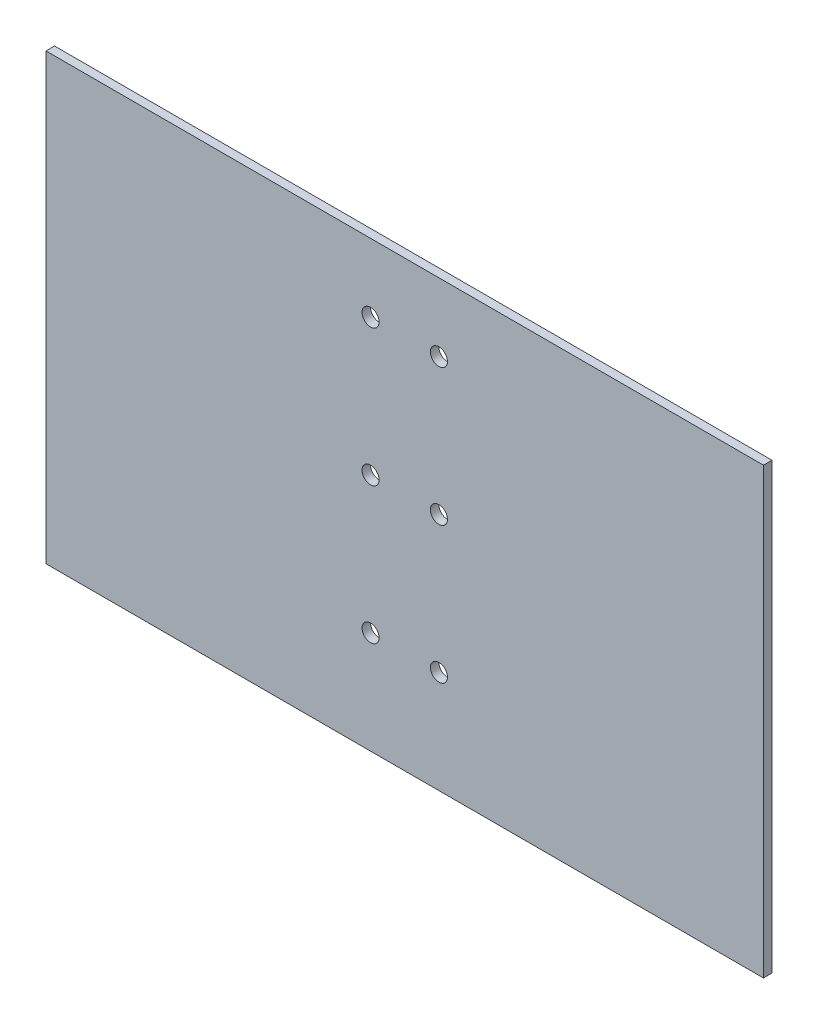
SolidWorks part; units mm, degrees
ref_plane "Front Plane" through (0, 0, 0) normal (0, 0, 1) x (1, 0, 0)
ref_plane "Top Plane" through (0, 0, 0) normal (0, 1, 0) x (1, 0, 0)
ref_plane "Right Plane" through (0, 0, 0) normal (1, 0, 0) x (0, 0, -1)
sketch "Sketch1" plane through (0, 0, 0) normal (0, 0, 1) x (1, 0, 0)
  line L1 (-127, -76.2) -> (127, -76.2)
  line L2 (-127, -76.2) -> (-127, 76.2)
  line L3 (-127, 76.2) -> (127, 76.2)
  line L4 (127, -76.2) -> (127, 76.2)
  line L5 (-127, -76.2) -> (127, 76.2) construction
  line L6 (-127, 76.2) -> (127, -76.2) construction
  circle A0 centre (0, 0) radius 53.34
  dimension "D1" = 127
  dimension "D3" = 106.68
  dimension "D2" = 76.2
extrude "Boss-Extrude1" add sketch "Sketch1" along normal blind 6.35
hole_wizard "3/8 Clearance Hole1" [suppressed] positions "Sketch5" profile "Sketch6" hole size "3/8" standard "ANSI Inch"
sketch "Sketch5" plane through (0, 0, 6.35) normal (0, 0, 1) x (1, 0, 0)
  circle A0 centre (0, 0) radius 67.31
  point P10 (-67.31, 0)
  point P18 (-54.4549, 39.5638)
  point P19 (-20.7999, 64.0156)
  point P20 (20.7999, 64.0156)
  point P21 (54.4549, 39.5638)
  point P22 (67.31, 0)
  point P23 (54.4549, -39.5638)
  point P24 (20.7999, -64.0156)
  point P25 (-20.7999, -64.0156)
  point P26 (-54.4549, -39.5638)
  dimension "D1" = 134.62
  dimension "D2" = 10
sketch "Sketch6" plane through (-54.4549, -39.5638, 6.35) normal (1, 0, 0) x (0, -1, 0)
  line L0 (0, 0) -> (0, 6.35)
  line L1 (0, 6.35) -> (5.0419, 6.35)
  line L2 (5.0419, 6.35) -> (5.0419, 0.635)
  line L3 (5.0419, 0.635) -> (5.6769, 0)
  line L5 (5.6769, 0) -> (0, 0)
  line L6 (-5.0419, 0.635) -> (-5.6769, 0) construction
  line L11 (0, -6.35) -> (0, 107.95) construction
  dimension "Thru Hole Dia." = 10.0838
  dimension "Thru Hole Depth" = 6.35
  dimension "Near C'Sink Dia." = 11.3538
  dimension "Near C'Sink Angle" = 90
hole_wizard "#4 Clearance Hole1" [suppressed] positions "Sketch8" profile "Sketch10" hole size "#4" standard "ANSI Inch"
sketch "Sketch8" plane through (0, 0, 0) normal (0, 0, -1) x (-1, 0, 0)
  line L0 (127, 0) -> (-127, 0) construction
  line L1 (127, 76.2) -> (127, -76.2) construction
  line L2 (-127, -76.2) -> (-127, 76.2) construction
  line L4 (0, 76.2) -> (0, -76.2) construction
  line L5 (-127, 76.2) -> (127, 76.2) construction
  line L6 (127, -76.2) -> (-127, -76.2) construction
  point P9 (67.31, 64.0156)
  point P30 (67.31, -64.0156)
  point P31 (-67.31, -64.0156)
  point P32 (-67.31, 64.0156)
  dimension "D1" = 67.31
  dimension "D2" = 12.1844
sketch "Sketch10" plane through (-67.31, 64.0156, 0) normal (1, 0, 0) x (0, 1, 0)
  line L0 (0, 0) -> (0, 6.35)
  line L1 (0, 6.35) -> (1.6319, 6.35)
  line L2 (1.6319, 6.35) -> (1.6319, 0)
  line L5 (1.6319, 0) -> (0, 0)
  line L11 (0, -6.35) -> (0, 107.95) construction
  dimension "Thru Hole Dia." = 3.2639
  dimension "Thru Hole Depth" = 6.35
sketch "Sketch11" plane through (0, 0, 0) normal (0, 0, -1) x (-1, 0, 0)
  line L0 (127, 76.2) -> (127, -76.2) construction
  line L1 (127, 76.2) -> (127, -76.2) construction
  line L2 (127, 0) -> (107.95, 0) construction
  line L4 (0, 76.2) -> (0, -76.2) construction
  line L5 (-127, 76.2) -> (127, 76.2) construction
  line L6 (127, -76.2) -> (-127, -76.2) construction
  circle A0 centre (107.95, 0) radius 4.1656
  circle A1 centre (-107.95, 0) radius 4.1656
  dimension "D1" = 8.3312
  dimension "D2" = 19.05
extrude "Cut-Extrude1" [suppressed] cut sketch "Sketch11" against normal through all
sketch "Sketch12" plane through (0, 0, 6.35) normal (0, 0, 1) x (1, 0, 0)
  line L0 (127, 76.2) -> (-127, 76.2) construction
  line L1 (101.6, -76.2) -> (-101.6, -76.2)
  line L2 (101.6, -76.2) -> (101.6, 76.2)
  line L3 (101.6, 76.2) -> (-101.6, 76.2)
  line L4 (-101.6, -76.2) -> (-101.6, 76.2)
  line L5 (101.6, -76.2) -> (-101.6, 76.2) construction
  line L6 (101.6, 76.2) -> (-101.6, -76.2) construction
  line L7 (-127, 76.2) -> (-127, -76.2) construction
  point P0 (0, 0)
  dimension "D1" = 25.4
extrude "Cut-Extrude2" [suppressed] cut sketch "Sketch12" against normal through all flip side to cut
sketch "Sketch13" plane through (0, 0, 6.35) normal (0, 0, 1) x (1, 0, 0)
  circle A0 centre (0, 0) radius 53.34 construction
  circle A1 centre (0, 0) radius 53.34
extrude "Boss-Extrude2" add sketch "Sketch13" against normal blind 6.35
sketch "Sketch16" [suppressed] plane through (0, 0, 6.35) normal (0, 0, 1) x (1, 0, 0)
  circle A1 centre (0, 0) radius 63.5
  dimension "D1" = 127
extrude "Cut-Extrude3" [suppressed] cut sketch "Sketch16" against normal blind 6.35
sketch "Sketch17" [suppressed] plane through (0, 0, 6.35) normal (0, 0, 1) x (1, 0, 0)
  line L0 (0, 139.7) -> (0, -139.7) construction
  line L1 (-139.7, 139.7) -> (-146.05, 139.7)
  line L2 (-139.7, 139.7) -> (-139.7, -76.2)
  line L3 (-139.7, -76.2) -> (-146.05, -76.2)
  line L4 (-146.05, 139.7) -> (-146.05, -76.2)
  line L5 (139.7, 139.7) -> (-139.7, 139.7) construction
  line L6 (-139.7, -139.7) -> (139.7, -139.7) construction
  line L7 (139.7, -76.2) -> (146.05, -76.2)
  line L8 (146.05, 139.7) -> (146.05, -76.2)
  line L9 (139.7, 139.7) -> (146.05, 139.7)
  line L10 (139.7, 139.7) -> (139.7, -76.2)
  dimension "D1" = 6.35
extrude "Boss-Extrude3" [suppressed] add sketch "Sketch17" against normal blind 12.7
sketch "Sketch18" [suppressed] plane through (0, 0, 6.35) normal (0, 0, 1) x (1, 0, 0)
  line L0 (-146.05, 25.4) -> (146.05, 25.4) construction
  line L1 (-146.05, 127) -> (-146.05, -76.2) construction
  line L2 (146.05, -76.2) -> (146.05, 127) construction
  line L3 (0, 127) -> (0, -127) construction
  line L4 (146.05, 127) -> (-146.05, 127) construction
  line L5 (-139.7, -127) -> (139.7, -127) construction
  circle A0 centre (-127, 25.4) radius 4.1656
  circle A1 centre (127, 25.4) radius 4.1656
  dimension "D1" = 8.3312
  dimension "D2" = 19.05
extrude "Cut-Extrude4" [suppressed] cut sketch "Sketch18" against normal through all
sketch "Sketch21" plane through (0, 0, 6.35) normal (0, 0, 1) x (1, 0, 0)
  line L12 (127, -76.2) -> (127, 76.2) construction
  line L13 (-127, -76.2) -> (127, -76.2) construction
  line L14 (-127, 76.2) -> (-127, -76.2) construction
  line L15 (127, 76.2) -> (-127, 76.2) construction
  line L20 (-215.9, -127) -> (215.9, -127)
  line L21 (215.9, -127) -> (215.9, 152.4)
  line L22 (-215.9, 152.4) -> (-215.9, -127)
  line L23 (215.9, 152.4) -> (-215.9, 152.4)
  line L24 (127, -76.2) -> (127, 76.2)
  line L25 (-127, -76.2) -> (127, -76.2)
  line L26 (-127, 76.2) -> (-127, -76.2)
  line L27 (127, 76.2) -> (-127, 76.2)
  dimension "D1" = 88.9
  dimension "D2" = 88.9
  dimension "D3" = 50.8
  dimension "D4" = 76.2
extrude "Boss-Extrude5" add sketch "Sketch21" against normal blind 6.35
sketch "Sketch19" plane through (0, 0, 6.35) normal (0, 0, 1) x (1, 0, 0)
  line L0 (0, 152.4) -> (0, -127) construction
  line L3 (-25.4, 152.4) -> (-25.4, -127) construction
  line L5 (215.9, 152.4) -> (-215.9, 152.4) construction
  line L6 (-215.9, -127) -> (215.9, -127) construction
  circle A0 centre (-25.4, 127) radius 6.35
  circle A1 centre (-25.4, 25.4) radius 6.35
  circle A2 centre (25.4, 25.4) radius 6.35
  circle A3 centre (25.4, 127) radius 6.35
  circle A4 centre (-25.4, -76.2) radius 6.35
  circle A5 centre (25.4, -76.2) radius 6.35
  dimension "D2" = 12.7
  dimension "D1" = 25.4
  dimension "D3" = 2
  dimension "D5" = 101.6
  dimension "D6" = 101.6
  dimension "D7" = 25.4
  dimension "D4" = 2
extrude "Cut-Extrude5" cut sketch "Sketch19" against normal through all
sketch "Sketch22" [suppressed] plane through (0, 0, 6.35) normal (0, 0, 1) x (1, 0, 0)
  line L0 (-27.94, 109.855) -> (27.94, 109.855) construction
  line L1 (0, 109.855) -> (-84.1538, -70.6134) construction
  line L2 (-84.1538, -70.6134) -> (84.1538, -70.6134) construction
  line L3 (84.1538, -70.6134) -> (0, 109.855) construction
  line L4 (-102.1133, -49.2102) -> (-66.1943, -92.0167) construction
  line L5 (0, 109.855) -> (0, -139.7) construction
  line L6 (-139.7, -139.7) -> (139.7, -139.7) construction
  line L7 (102.1133, -49.2102) -> (66.1943, -92.0167) construction
  circle A0 centre (0, 0) radius 109.855 construction
  point P5 (0, 109.855)
  point P11 (-84.1538, -70.6134)
  dimension "D1" = 219.71
  dimension "D2" = 55.88
  dimension "D3" = 65
  dimension "D4" = 55.88
hole_wizard "#8 Clearance Hole1" [suppressed] positions "3DSketch1" profile "Sketch23" hole size "#8" standard "ANSI Inch"
sketch3d "3DSketch1"
  point P0 (-27.94, 109.855, 6.35)
  point P3 (27.94, 109.855, 6.35)
  point P6 (102.1133, -49.2102, 6.35)
  point P9 (66.1943, -92.0167, 6.35)
  point P12 (-66.1943, -92.0167, 6.35)
  point P15 (-102.1133, -49.2102, 6.35)
sketch "Sketch23" plane through (-27.94, 109.855, 6.35) normal (1, 0, 0) x (0, -1, 0)
  line L0 (0, 0) -> (0, 13.97)
  line L1 (0, 13.97) -> (2.2479, 12.6193)
  line L2 (2.2479, 12.6193) -> (2.2479, 0)
  line L5 (2.2479, 0) -> (0, 0)
  line L10 (0, 13.97) -> (-2.2479, 12.6193) construction
  line L11 (0, -6.35) -> (0, 107.95) construction
  dimension "Hole Dia." = 4.4958
  dimension "Hole Depth" = 13.97
  dimension "Drill Angle" = 118
sketch "Sketch25" plane through (0, 0, 6.35) normal (0, 0, 1) x (1, 0, 0)
  line L11 (215.9, -127) -> (215.9, 152.4) construction
  line L12 (-266.7, -152.4) -> (266.7, -152.4)
  line L13 (-266.7, -152.4) -> (-266.7, 177.8)
  line L14 (-266.7, 177.8) -> (266.7, 177.8)
  line L15 (266.7, -152.4) -> (266.7, 177.8)
  line L16 (-215.9, 152.4) -> (-215.9, -127) construction
  line L17 (215.9, 152.4) -> (-215.9, 152.4) construction
  line L18 (-215.9, -127) -> (215.9, -127) construction
  line L19 (-215.9, 152.4) -> (215.9, 152.4)
  line L20 (215.9, 152.4) -> (215.9, -127)
  line L21 (215.9, -127) -> (-215.9, -127)
  line L22 (-215.9, -127) -> (-215.9, 152.4)
  dimension "D1" = 50.8
  dimension "D2" = 50.8
  dimension "D3" = 25.4
  dimension "D4" = 25.4
extrude "Boss-Extrude7" add sketch "Sketch25" against normal blind 6.35
